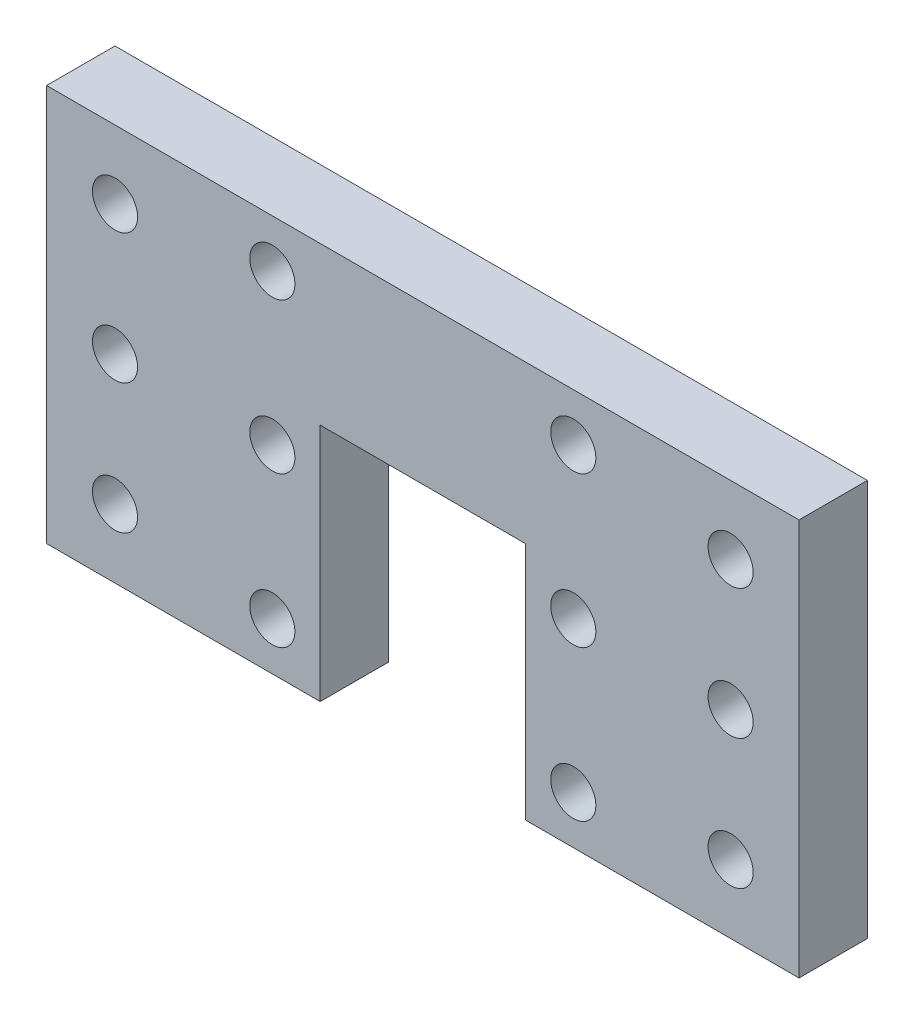
SolidWorks part; units mm, degrees
ref_plane "Front Plane" through (0, 0, 0) normal (0, 0, 1) x (1, 0, 0)
ref_plane "Top Plane" through (0, 0, 0) normal (0, 1, 0) x (1, 0, 0)
ref_plane "Right Plane" through (0, 0, 0) normal (1, 0, 0) x (0, 0, -1)
sketch "Sketch1" plane through (0, 0, 0) normal (0, 0, 1) x (1, 0, 0)
  line L0 (55, 0) -> (15, 0)
  line L1 (40, 0) -> (120, 0) construction
  line L2 (15, 0) -> (15, 35)
  line L3 (15, 35) -> (-15, 35)
  line L4 (-15, 35) -> (-15, 0)
  line L5 (-15, 0) -> (-55, 0)
  line L6 (-120, 0) -> (-40, 0) construction
  line L7 (-55, 0) -> (-55, 58)
  line L8 (-55, 58) -> (55, 58)
  line L9 (55, 58) -> (55, 0)
  line L10 (45, 0) -> (45, 10) construction
  line L11 (45, 10) -> (45, 48) construction
  line L12 (45, 48) -> (45, 58) construction
  line L13 (45, 10) -> (55, 10) construction
  line L14 (0, 58) -> (0, 0) construction
  line L15 (45, 10) -> (35, 10) construction
  line L17 (35, 605) -> (35, 5) construction
  line L18 (29, 7) -> (22, 7) construction
  line L19 (29, 0) -> (29, 58) construction
  line L20 (22, 7) -> (15, 7) construction
  line L21 (22, 0) -> (22, 7) construction
  line L22 (22, 7) -> (22, 51) construction
  line L23 (22, 51) -> (22, 58) construction
  point P27 (-45, 48)
  point P28 (-45, 10)
  point P35 (-22, 51)
  point P38 (-22, 7)
  point P39 (45, 29)
  point P40 (22, 29)
  point P41 (-22, 29)
  point P42 (-45, 29)
  dimension "D1" = 20
extrude "Boss-Extrude1" add sketch "Sketch1" along normal blind 10 contours L9 L0 L2 L3 L4 L5 L7 L8
hole_wizard "M6 Clearance Hole" positions "Sketch4" profile "Sketch5" hole size "M6" standard "ISO" end condition through all
sketch "Sketch4" plane through (559.8458, 1460.8861, 10) normal (0, 0, 1) x (-1, 0, 0)
  point P0 (514.8458, 1450.8861)
  point P3 (514.8458, 1412.8861)
  point P6 (537.8458, 1453.8861)
  point P9 (537.8458, 1409.8861)
  point P12 (581.8458, 1453.8861)
  point P15 (581.8458, 1409.8861)
  point P18 (604.8458, 1450.8861)
  point P21 (604.8458, 1412.8861)
  point P24 (514.8458, 897.4716)
  point P27 (537.8458, 897.4716)
  point P30 (581.8458, 897.4716)
  point P33 (604.8458, 897.4716)
  point P36 (394.7524, 1482.1561)
  point P40 (514.8458, 1431.8861)
  point P43 (537.8458, 1431.8861)
  point P47 (581.8458, 1431.8861)
  point P53 (604.8458, 1431.8861)
sketch "Sketch5" plane through (45, 10, 10) normal (1, 0, 0) x (0, -1, 0)
  line L0 (0, 0) -> (0, 10)
  line L1 (0, 10) -> (3.3, 10)
  line L2 (3.3, 10) -> (3.3, 0)
  line L3 (3.3, 0) -> (0, 0)
  line L4 (0, -6.35) -> (0, 107.95) construction
  dimension "Thru Hole Dia." = 6.6
  dimension "Thru Hole Depth" = 10
